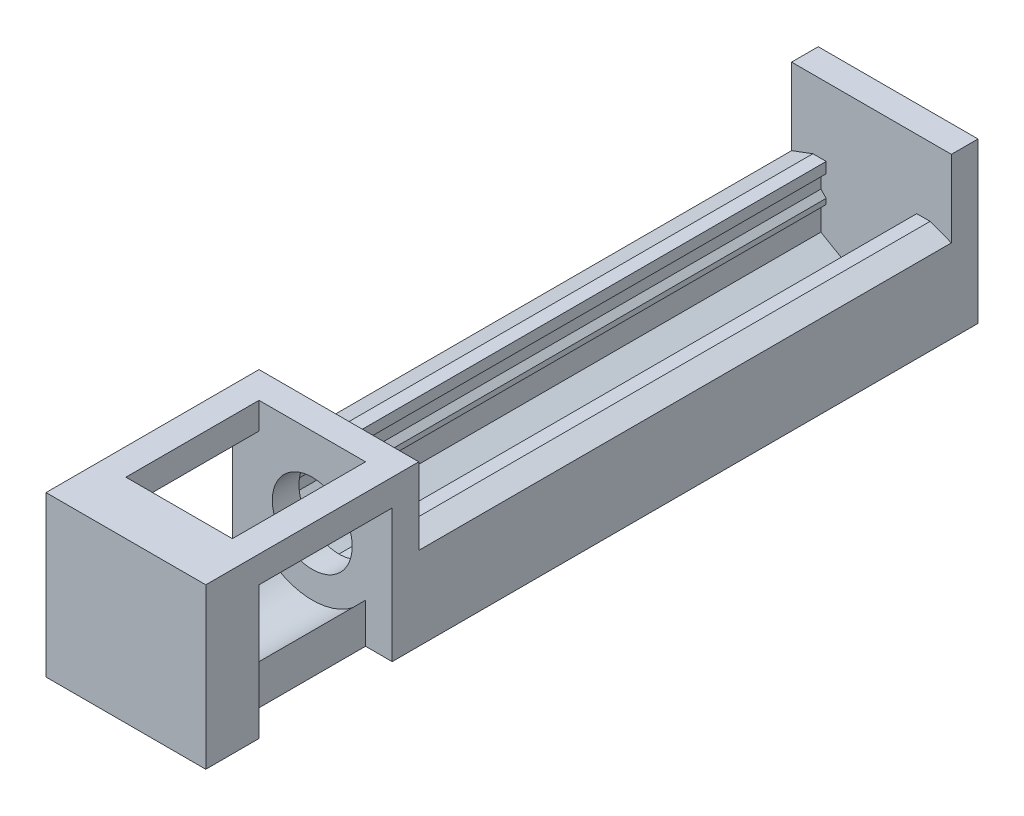
SolidWorks part; units mm, degrees
ref_plane "Front Plane" through (0, 0, 0) normal (0, 0, 1) x (1, 0, 0)
ref_plane "Top Plane" through (0, 0, 0) normal (0, 1, 0) x (1, 0, 0)
ref_plane "Right Plane" through (0, 0, 0) normal (1, 0, 0) x (0, 0, -1)
sketch "Sketch1" plane through (0, 0, 0) normal (0, 0, 1) x (1, 0, 0)
  line L0 (-30, 30) -> (30, 30)
  line L1 (-20, -20) -> (20, -20) construction
  line L2 (-20, -20) -> (-20, 20) construction
  line L3 (-20, 20) -> (20, 20) construction
  line L4 (20, -20) -> (20, 20) construction
  line L5 (-20, -20) -> (20, 20) construction
  line L6 (-20, 20) -> (20, -20) construction
  line L7 (30, -30) -> (30, 30)
  line L8 (-30, -30) -> (30, -30)
  line L9 (-30, -30) -> (-30, 30)
  point P0 (0, 0)
  dimension "D1" = 40
  dimension "D2" = 40
  dimension "D3" = 10
extrude "Boss-Extrude1" add sketch "Sketch1" along normal blind 80
sketch "Sketch5" plane through (0, 0, 0) normal (0, 0, -1) x (-1, 0, 0)
  line L9 (-30, 30) -> (30, 30)
  line L10 (-30, 30) -> (-30, -30)
  line L11 (-30, -30) -> (30, -30)
  line L12 (30, 30) -> (30, -30)
  line L14 (-30, 30) -> (-20, 30)
  line L15 (-30, 30) -> (-30, 20)
  line L18 (-30, 20) -> (-20, 20)
  line L19 (-20, 30) -> (-20, 20)
  line L20 (30, 30) -> (20, 30)
  line L22 (30, 30) -> (30, 20)
  line L23 (30, 20) -> (20, 20)
  line L24 (20, 30) -> (20, 20)
  line L25 (-20, -30) -> (20, -30)
  line L26 (-20, -30) -> (-20, -15)
  line L28 (20, -30) -> (20, -15)
  arc A0 (-20, -15) -> (20, -15) centre (0, 0) ccw
  dimension "D1" = 10
  dimension "D2" = 10
  dimension "D3" = 15
  dimension "D4" = 10
  dimension "D5" = 10
extrude "Cut-Extrude3" cut sketch "Sketch5" against normal offset from surface (60 mm away) 20
sketch "Sketch6" plane through (0, 0, 0) normal (0, 0, -1) x (-1, 0, 0)
  line L5 (-30, 30) -> (30, 30)
  line L6 (-30, 30) -> (-30, -30)
  line L7 (-30, -30) -> (30, -30)
  line L8 (30, 30) -> (30, -30)
extrude "Boss-Extrude3" add sketch "Sketch6" against normal blind 10
sketch "Sketch7" plane through (0, 0, 0) normal (0, 0, -1) x (-1, 0, 0)
  circle A0 centre (0, 0) radius 15
  dimension "D1" = 30
extrude "Cut-Extrude4" cut sketch "Sketch7" against normal blind 10
sketch "Sketch8" plane through (0, 0, 0) normal (0, 0, -1) x (-1, 0, 0)
  line L1 (0, 0) -> (0, -30) construction
  line L4 (-30, -25) -> (30, -25)
  line L7 (22, 4.1962) -> (30, 1.1962)
  line L9 (30, -30) -> (-30, -30)
  line L11 (-30, -30) -> (-30, 30) construction
  line L12 (30, -30) -> (30, 1.1962)
  line L13 (30, 30) -> (30, -30) construction
  line L14 (-10, -25) -> (-19, -19.8038)
  line L15 (-19, -19.8038) -> (-19, -11.8038)
  line L16 (-19, -11.8038) -> (-17, -9.8038)
  line L17 (-17, -9.8038) -> (-17, -7.8038)
  line L18 (-17, -7.8038) -> (-19, -5.8038)
  line L19 (-19, -5.8038) -> (-19, 0.1962)
  line L20 (-19, 0.1962) -> (-17, 0.1962)
  line L21 (-17, 0.1962) -> (-17, 4.1962)
  line L22 (-17, 4.1962) -> (-22, 4.1962)
  line L23 (-22, 4.1962) -> (-30, 1.1962)
  line L24 (-30, 1.1962) -> (-30, -30)
  line L25 (17, 4.1962) -> (22, 4.1962)
  line L26 (17, 0.1962) -> (17, 4.1962)
  line L27 (19, 0.1962) -> (17, 0.1962)
  line L28 (19, -5.8038) -> (19, 0.1962)
  line L29 (17, -7.8038) -> (19, -5.8038)
  line L30 (17, -9.8038) -> (17, -7.8038)
  line L31 (19, -11.8038) -> (17, -9.8038)
  line L32 (19, -19.8038) -> (19, -11.8038)
  line L33 (10, -25) -> (19, -19.8038)
  line L34 (30, 1.1962) -> (30, -25)
  line L35 (30, -30) -> (30, -25)
  line L36 (30, -30) -> (30, -25)
  line M9 (-30, 30) -> (-30, -30)
  line M10 (-30, -30) -> (30, -30)
  line M11 (30, -30) -> (30, 30)
  dimension "D1" = 5
  dimension "D2" = 20
  dimension "D3" = 9
  dimension "D4" = 6
  dimension "D5" = 2
  dimension "D6" = 2
  dimension "D7" = 2
  dimension "D8" = 8
  dimension "D9" = 30
  dimension "D10" = 4
  dimension "D11" = 3
  dimension "D12" = 8
extrude "Boss-Extrude4" add sketch "Sketch8" along normal blind 200 contours L22 L23 L4 L14 L15 L16 L17 L18 L19 L20 L21 M9 | L33 L4 L7 L25 L26 L27 L28 L29 L30 L31 L32 M11 | L4 L1 L9 M11 | L1 L4 M9 M10
sketch "Sketch10" plane through (0, -30, 0) normal (0, -1, 0) x (1, 0, 0)
  line L6 (-30, -200) -> (30, -200)
  line L7 (-30, -200) -> (-30, -210)
  line L8 (-30, -210) -> (30, -210)
  line L9 (30, -200) -> (30, -210)
  dimension "D1" = 60
  dimension "D2" = 10
extrude "Boss-Extrude5" add sketch "Sketch10" against normal blind 60
